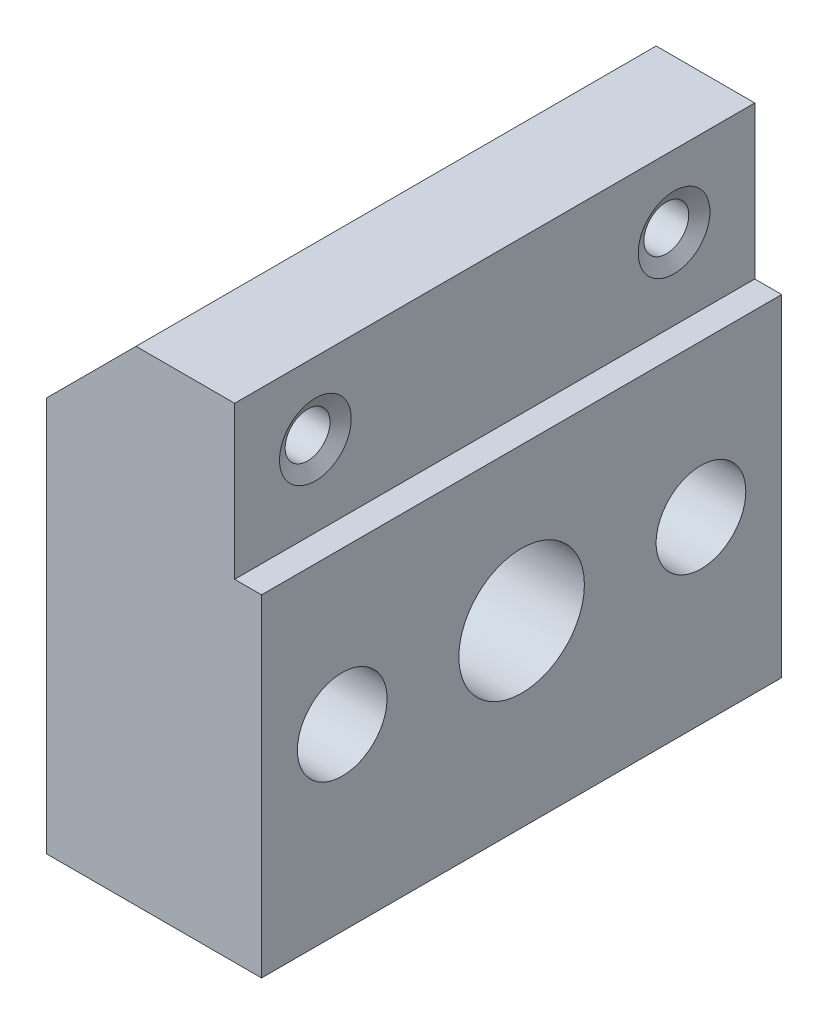
SolidWorks part; units mm, degrees
material "1.0503 (C45)"
ref_plane "Front Plane" through (0, 0, 0) normal (0, 0, 1) x (1, 0, 0)
ref_plane "Top Plane" through (0, 0, 0) normal (0, 1, 0) x (1, 0, 0)
ref_plane "Right Plane" through (0, 0, 0) normal (1, 0, 0) x (0, 0, -1)
sketch "Esquisse1" plane through (0, 0, 0) normal (0, 0, 1) x (1, 0, 0)
  line L0 (0, 0) -> (0, 37)
  line L1 (0, 37) -> (-3, 37)
  line L2 (-3, 37) -> (-3, 54)
  line L3 (-3, 54) -> (-14, 54)
  line L4 (-24, 44) -> (-24, 0)
  line L5 (-24, 0) -> (0, 0)
  line L6 (-14, 54) -> (-24, 44)
  point P5 (-24, 54)
  dimension "D1" = 37
  dimension "D2" = 3
  dimension "D3" = 17
  dimension "D4" = 21
extrude "Boss.-Extru.1" add sketch "Esquisse1" along normal blind 58
sketch "Esquisse2" plane through (0, 0, 0) normal (1, 0, 0) x (0, 0, -1)
  line L0 (0, 0) -> (0, 37) construction
  line L1 (-58, 54) -> (0, 54) construction
  line L2 (-29, 37) -> (-29, 17.8144) construction
  line L3 (-58, 37) -> (0, 37) construction
  circle A0 centre (-9, 20) radius 5
  circle A1 centre (-49, 20) radius 5
  dimension "D1" = 10
  dimension "D2" = 9
  dimension "D3" = 34
extrude "Enlèv. mat.-Extru.1" cut sketch "Esquisse2" against normal through all
hole_wizard "Trou taraudé M161" positions "Esquisse3" profile "Esquisse4" tap size "M16" standard "ISO" end condition through all
sketch "Esquisse3" plane through (0, 0, 0) normal (1, 0, 0) x (0, 0, -1)
  line L0 (0, 0) -> (0, 37) construction
  line L1 (-58, 0) -> (0, 0) construction
  point P0 (-29, 20)
  dimension "D1" = 29
  dimension "D2" = 20
sketch "Esquisse4" plane through (0, 20, 29) normal (0, 1, 0) x (0, 0, -1)
  line L0 (0, 0) -> (0, 24)
  line L1 (0, 24) -> (7, 24)
  line L2 (7, 24) -> (7, 0)
  line L5 (7, 0) -> (0, 0)
  line L11 (0, -6.35) -> (0, 107.95) construction
  dimension "Diamètre du trou pour taraudage jusqu'au prochain" = 14
  dimension "Profondeur du trou pour taraudage jusqu'au prochain" = 24
cosmetic thread "Filetage de perçage1" parameters "D2"=16
hole_wizard "Trou taraudé M61" positions "Esquisse7" profile "Esquisse8" tap size "M6" standard "ISO"
sketch "Esquisse7" plane through (-3, 0, 0) normal (1, 0, 0) x (0, 0, -1)
  line L0 (0, 37) -> (0, 54) construction
  line L1 (-58, 54) -> (0, 54) construction
  point P0 (-9, 46)
  dimension "D1" = 9
  dimension "D2" = 8
sketch "Esquisse8" plane through (-3, 46, 9) normal (0, 1, 0) x (0, 0, -1)
  line L0 (0, 0) -> (0, 16.5022)
  line L1 (0, 16.5022) -> (2.5, 15)
  line L2 (2.5, 15) -> (2.5, 0.866)
  line L3 (2.5, 0.866) -> (4, 0)
  line L5 (4, 0) -> (0, 0)
  line L6 (-2.5, 0.866) -> (-4, 0) construction
  line L10 (0, 16.5022) -> (-2.5, 15) construction
  line L11 (0, -6.35) -> (0, 107.95) construction
  dimension "Diamètre du trou pour taraudage" = 5
  dimension "Profondeur du trou pour taraudage" = 15
  dimension "Diamètre du fraisage entrant" = 8
  dimension "Angle du fraisage entrant" = 120
  dimension "Angle de pointe" = 118
cosmetic thread "Filetage de perçage2" parameters "D1"=12, "D2"=6
pattern_linear "Répétition linéaire1" count 2 spacing 40 along (0, 0, 1) of "Trou taraudé M61"
